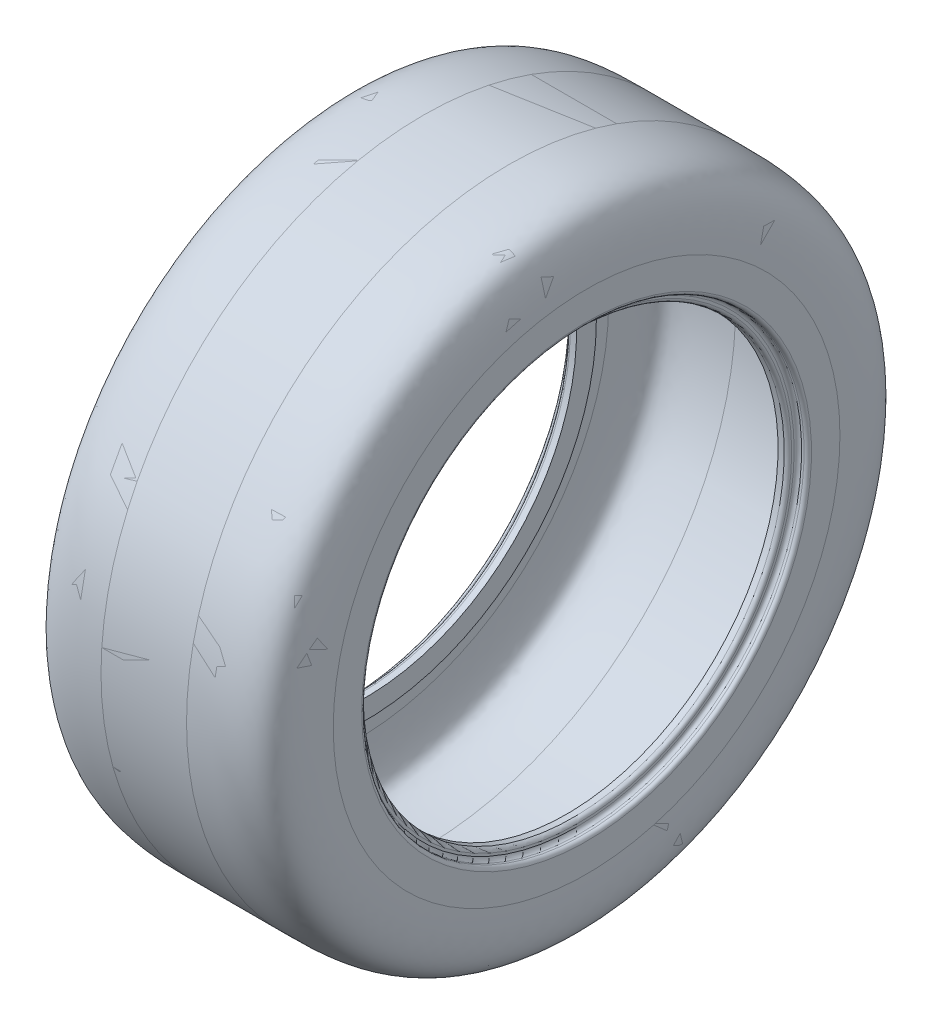
SolidWorks part; units mm, degrees
material "EPDM 60 Durometer"
ref_plane "Front Plane" through (0, 0, 0) normal (0, 0, 1) x (1, 0, 0)
ref_plane "Top Plane" through (0, 0, 0) normal (0, 1, 0) x (1, 0, 0)
ref_plane "Right Plane" through (0, 0, 0) normal (1, 0, 0) x (0, 0, -1)
sketch "Sketch1" plane through (0, 0, 0) normal (0, 0, 1) x (1, 0, 0)
  line L0 (0, 0) -> (0, 260.35) construction
  line L1 (0, 260.35) -> (-34.544, 260.35)
  line L3 (-81.407, 170.688) -> (-89.408, 170.688)
  line L4 (-89.408, 170.688) -> (-89.408, 178.689)
  line L5 (-89.408, 178.689) -> (-97.409, 178.689)
  line L6 (-97.409, 178.689) -> (-97.409, 204.6732)
  line L7 (-97.409, 181.6723) -> (-97.409, 254.7212) construction
  line L8 (-306.9421, 260.35) -> (-223.5792, 260.35) construction
  line L9 (-89.408, 186.69) -> (-89.408, 204.6732)
  line L10 (-81.407, 186.69) -> (-89.408, 186.69)
  line L11 (-81.407, 178.689) -> (-81.407, 186.69)
  line L14 (-8.001, 252.349) -> (-34.544, 252.349)
  line L15 (-81.407, 178.689) -> (-81.407, 170.688)
  line L16 (-8.001, 252.349) -> (0, 252.349)
  line L17 (0, 170.688) -> (-89.408, 170.688) construction
  line L18 (-8.001, 178.689) -> (-81.407, 178.689) construction
  line L19 (-8.001, 252.349) -> (-8.001, 178.689) construction
  line L20 (0, 260.35) -> (0, 170.688) construction
  line L21 (0, 260.35) -> (0, 252.349)
  line L22 (-86.3526, 252.5215) -> (-81.3978, 246.2257) construction
  line L23 (-81.407, 186.69) -> (-34.544, 186.69) construction
  line L24 (-34.544, 186.69) -> (-34.544, 252.349) construction
  line L25 (-81.3978, 246.2257) -> (-34.544, 186.69) construction
  spline S0 degree 3 poles (-34.544, 260.35) (-54.238, 260.35) (-96.8437, 260.2947) (-97.409, 229.2012) (-97.409, 204.6732) knots 0 0 0 0 0.500439 1 1 1 1
  spline S1 degree 1 poles (-34.544, 252.349) (-89.408, 204.6732) knots 0 0 1 1 construction
  spline S2 degree 3 poles (-34.544, 252.349) (-37.004, 252.349) (-41.9379, 252.3479) (-51.694, 252.2246) (-60.9756, 251.7439) (-69.0967, 250.6167) (-74.4013, 249.4128) (-78.2236, 248.033) (-80.6182, 246.7727) (-82.3681, 245.5656) (-83.9698, 244.0244) (-85.5796, 241.6613) (-87.0031, 238.2266) (-88.1027, 233.6696) (-88.8374, 227.9999) (-89.1749, 222.3943) (-89.3208, 217.4055) (-89.3811, 213.4181) (-89.4017, 209.888) (-89.4074, 206.9536) (-89.408, 205.4285) (-89.408, 204.6732) knots 0 0 0 0 0.0625 0.125 0.25 0.3125 0.375 0.4375 0.478344 0.509594 0.5625 0.625 0.6875 0.75 0.8125 0.875 0.90625 0.9375 0.96875 0.984375 1 1 1 1
  dimension "D10" = 103.9901
  dimension "D1" = 260.35
  dimension "D2" = 34.544
  dimension "D3" = 89.662
  dimension "D4" = 89.408
  dimension "D5" = 25.9842
  dimension "D6" = 75.7613
  dimension "D7" = 81.661
  dimension "D9" = 97.409
  dimension "D11" = 8.001
  dimension "D12" = 34.544
  dimension "D8" = 8.001
  dimension "D13" = 8.001
ref_axis "Wheel Axis" through (-120.1067, 0, 0) along (1, 0, 0)
revolve "Revolve1" add sketch "Sketch1" angle 360 about axis through (-120.1067, 0, 0) along (1, 0, 0)
fillet "Fillet1" radius 2.9972 3 edges at (-89.408, 0, 178.689) (-97.409, 0, 178.689) (-89.408, 0, 170.688)
mirror "Mirror1" of "Revolve1"
fillet "Fillet2" radius 2.9972 3 edges at (89.408, 0, 170.688) (89.408, 0, 178.689) (97.409, 0, 178.689)
surface "Surface-Knit1"
sketch "Centerpoint" plane through (0, 0, 0) normal (0, 1, 0) x (1, 0, 0)
  point P0 (0, 0)
